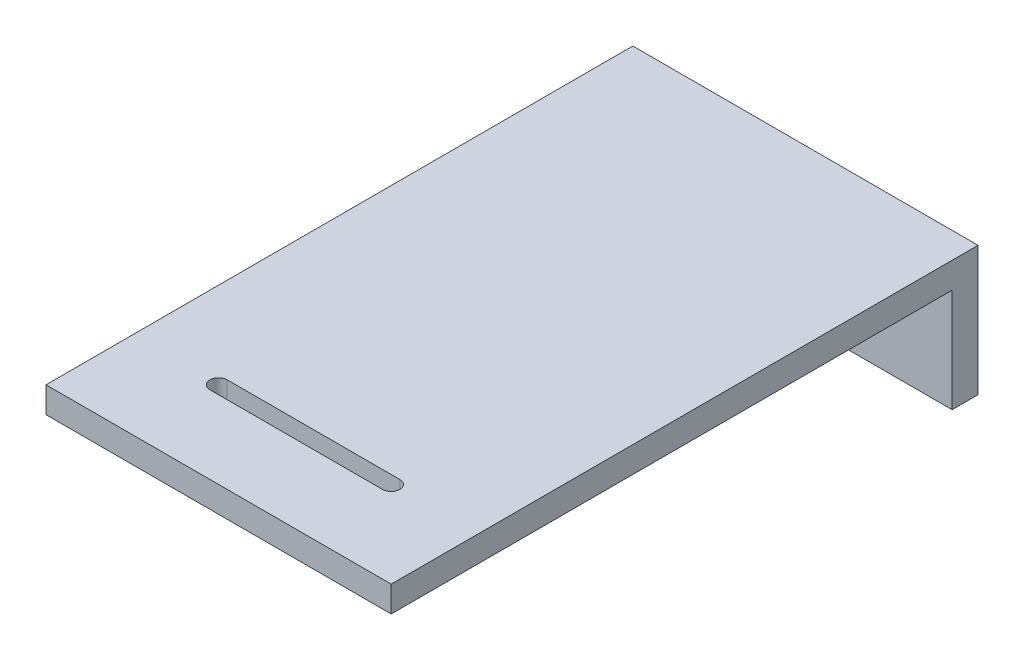
SolidWorks part; units mm, degrees
ref_plane "Front Plane" through (0, 0, 0) normal (0, 0, 1) x (1, 0, 0)
ref_plane "Top Plane" through (0, 0, 0) normal (0, 1, 0) x (1, 0, 0)
ref_plane "Right Plane" through (0, 0, 0) normal (1, 0, 0) x (0, 0, -1)
sketch "Sketch1" plane through (0, 0, 0) normal (0, 0, 1) x (1, 0, 0)
  line L1 (-20, 7.5) -> (20, 7.5)
  line L2 (-20, 7.5) -> (-20, -7.5)
  line L3 (-20, -7.5) -> (20, -7.5)
  line L4 (20, 7.5) -> (20, -7.5)
  line L5 (-20, 7.5) -> (20, -7.5) construction
  line L6 (-20, -7.5) -> (20, 7.5) construction
  circle A0 centre (-10, -2.5) radius 2
  circle A1 centre (10, -2.5) radius 2
  point P0 (0, 0)
  dimension "D3" = 4
  dimension "D1" = 40
  dimension "D2" = 15
  dimension "D5" = 10
  dimension "D6" = 5
  dimension "D4" = 2
extrude "Boss-Extrude1" add sketch "Sketch1" along normal blind 3
sketch "Sketch2" plane through (0, 0, 3) normal (0, 0, 1) x (1, 0, 0)
  line L0 (20, -7.5) -> (20, 7.5) construction
  line L1 (-20, 7.5) -> (20, 7.5)
  line L2 (-20, 7.5) -> (-20, 4.5)
  line L3 (-20, 4.5) -> (20, 4.5)
  line L4 (20, 7.5) -> (20, 4.5)
  dimension "D1" = 3
extrude "Boss-Extrude2" add sketch "Sketch2" along normal blind 65
sketch "Sketch3" plane through (0, 4.5, 0) normal (0, -1, 0) x (1, 0, 0)
  line L0 (-10, 58) -> (10, 58) construction
  line L1 (-10, 59) -> (10, 59)
  line L2 (-10, 57) -> (10, 57)
  line L3 (-20, 68) -> (-20, 3) construction
  line L4 (-20, 3) -> (20, 3) construction
  arc A0 (-10, 59) -> (-10, 57) centre (-10, 58) ccw
  arc A1 (10, 57) -> (10, 59) centre (10, 58) ccw
  point P2 (0, 58)
  dimension "D1" = 1
  dimension "D2" = 20
  dimension "D3" = 10
  dimension "D4" = 55
extrude "Cut-Extrude1" cut sketch "Sketch3" against normal blind 65
